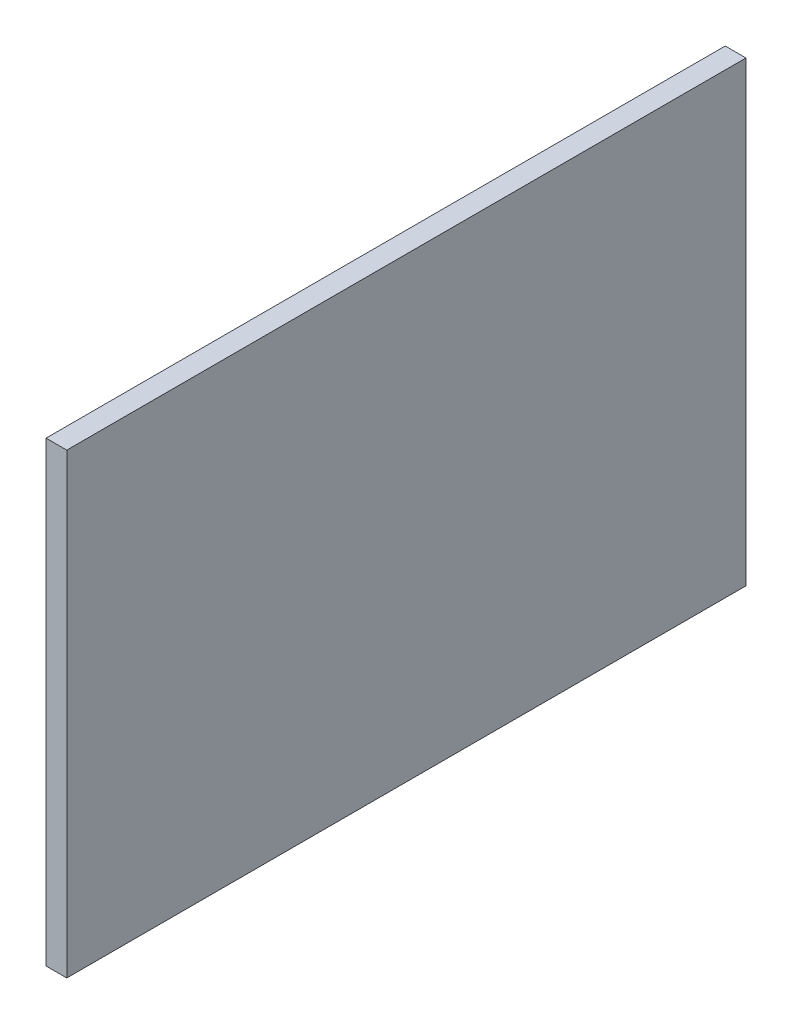
SolidWorks part; units mm, degrees
ref_plane "Front" through (0, 0, 0) normal (0, 0, 1) x (1, 0, 0)
ref_plane "Top" through (0, 0, 0) normal (0, 1, 0) x (1, 0, 0)
ref_plane "Right" through (0, 0, 0) normal (1, 0, 0) x (0, 0, -1)
sketch "Sketch1" plane through (0, 0, 0) normal (1, 0, 0) x (0, 0, -1)
  line L1 (0, 0) -> (104, 0)
  line L2 (0, 0) -> (0, 70)
  line L3 (0, 70) -> (104, 70)
  line L4 (104, 0) -> (104, 70)
  dimension "D1" = 104
  dimension "D2" = 70
extrude "Boss-Extrude1" add sketch "Sketch1" along normal blind 3.175
